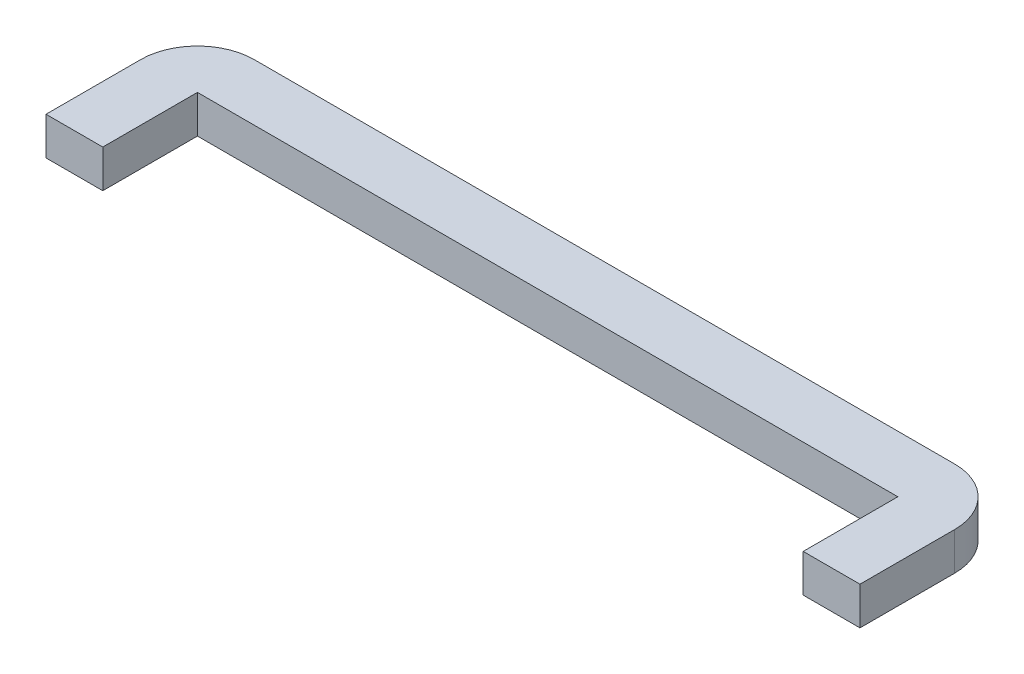
SolidWorks part; units mm, degrees
ref_plane "Front Plane" through (0, 0, 0) normal (0, 0, 1) x (1, 0, 0)
ref_plane "Top Plane" through (0, 0, 0) normal (0, 1, 0) x (1, 0, 0)
ref_plane "Right Plane" through (0, 0, 0) normal (1, 0, 0) x (0, 0, -1)
sketch "Sketch1" plane through (0, 0, 0) normal (0, 1, 0) x (1, 0, 0)
  line L1 (-21.5, -1.5) -> (21.5, -1.5)
  line L2 (-21.5, -1.5) -> (-21.5, 1.5)
  line L3 (-21.5, 1.5) -> (21.5, 1.5)
  line L4 (21.5, -1.5) -> (21.5, 1.5)
  line L5 (-21.5, -1.5) -> (21.5, 1.5) construction
  line L6 (-21.5, 1.5) -> (21.5, -1.5) construction
  line L7 (-21.5, -1.5) -> (-18.5, -1.5)
  line L8 (-21.5, -1.5) -> (-21.5, -6.5)
  line L9 (-21.5, -6.5) -> (-18.5, -6.5)
  line L10 (-18.5, -1.5) -> (-18.5, -6.5)
  line L11 (21.5, -1.5) -> (18.5, -1.5)
  line L12 (21.5, -1.5) -> (21.5, -6.5)
  line L13 (21.5, -6.5) -> (18.5, -6.5)
  line L14 (18.5, -1.5) -> (18.5, -6.5)
  point P0 (0, 0)
  dimension "D1" = 3
  dimension "D2" = 37
  dimension "D3" = 3
  dimension "D4" = 5
extrude "Boss-Extrude1" add sketch "Sketch1" along normal mid plane 2 contours L1 L4 L3 L2 | L10 L1 L8 L9 | L1 L14 L13 L12
fillet "Fillet1" radius 3 2 edges at (-21.5, 0, -1.5) (21.5, 0, -1.5)
